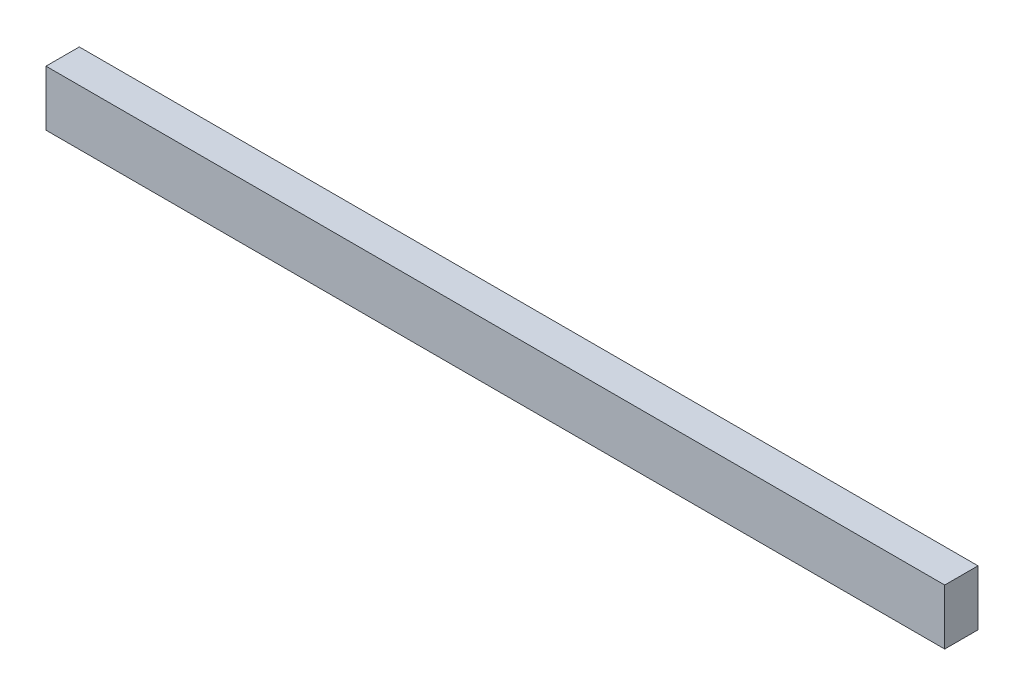
SolidWorks part; units mm, degrees
material "Pine"
ref_plane "Front Plane" through (0, 0, 0) normal (0, 0, 1) x (1, 0, 0)
ref_plane "Top Plane" through (0, 0, 0) normal (0, 1, 0) x (1, 0, 0)
ref_plane "Right Plane" through (0, 0, 0) normal (1, 0, 0) x (0, 0, -1)
sketch "Sketch1" plane through (0, 0, 0) normal (0, 1, 0) x (1, 0, 0)
  line L1 (-257.175, -9.525) -> (257.175, -9.525)
  line L2 (-257.175, -9.525) -> (-257.175, 9.525)
  line L3 (-257.175, 9.525) -> (257.175, 9.525)
  line L4 (257.175, -9.525) -> (257.175, 9.525)
  line L5 (-257.175, -9.525) -> (257.175, 9.525) construction
  line L6 (-257.175, 9.525) -> (257.175, -9.525) construction
  point P0 (0, 0)
  dimension "D1" = 19.05
  dimension "D2" = 514.35
extrude "Boss-Extrude1" add sketch "Sketch1" along normal blind 31.75
sketch "Sketch2" plane through (0, 0, -9.525) normal (0, 0, -1) x (-1, 0, 0)
  circle A0 centre (171.45, 15.875) radius 4.2164 construction
  circle A1 centre (85.725, 15.875) radius 4.2164 construction
  circle A2 centre (0, 15.875) radius 4.2164 construction
  circle A3 centre (-85.725, 15.875) radius 4.2164 construction
  circle A4 centre (-171.45, 15.875) radius 4.2164 construction
  circle A5 centre (171.45, 15.875) radius 4.2164
  circle A6 centre (85.725, 15.875) radius 4.2164
  circle A7 centre (0, 15.875) radius 4.2164
  circle A8 centre (-85.725, 15.875) radius 4.2164
  circle A9 centre (-171.45, 15.875) radius 4.2164
hole_wizard "1/8 (0.125) Diameter Hole1" positions "Sketch3" profile "Sketch5" hole size "1/8" standard "ANSI Inch"
sketch "Sketch3" plane through (0, 0, -9.525) normal (0, 0, -1) x (-1, 0, 0)
  point P0 (-171.45, 15.875)
  point P3 (-85.725, 15.875)
  point P6 (0, 15.875)
  point P9 (85.725, 15.875)
  point P12 (171.45, 15.875)
sketch "Sketch5" plane through (171.45, 15.875, -9.525) normal (1, 0, 0) x (0, 1, 0)
  line L0 (0, 0) -> (0, 12.0664)
  line L1 (0, 12.0664) -> (1.5875, 11.1125)
  line L2 (1.5875, 11.1125) -> (1.5875, 0)
  line L5 (1.5875, 0) -> (0, 0)
  line L10 (0, 12.0664) -> (-1.5875, 11.1125) construction
  line L11 (0, -6.35) -> (0, 107.95) construction
  dimension "Hole Dia." = 3.175
  dimension "Hole Depth" = 11.1125
  dimension "Drill Angle" = 118
